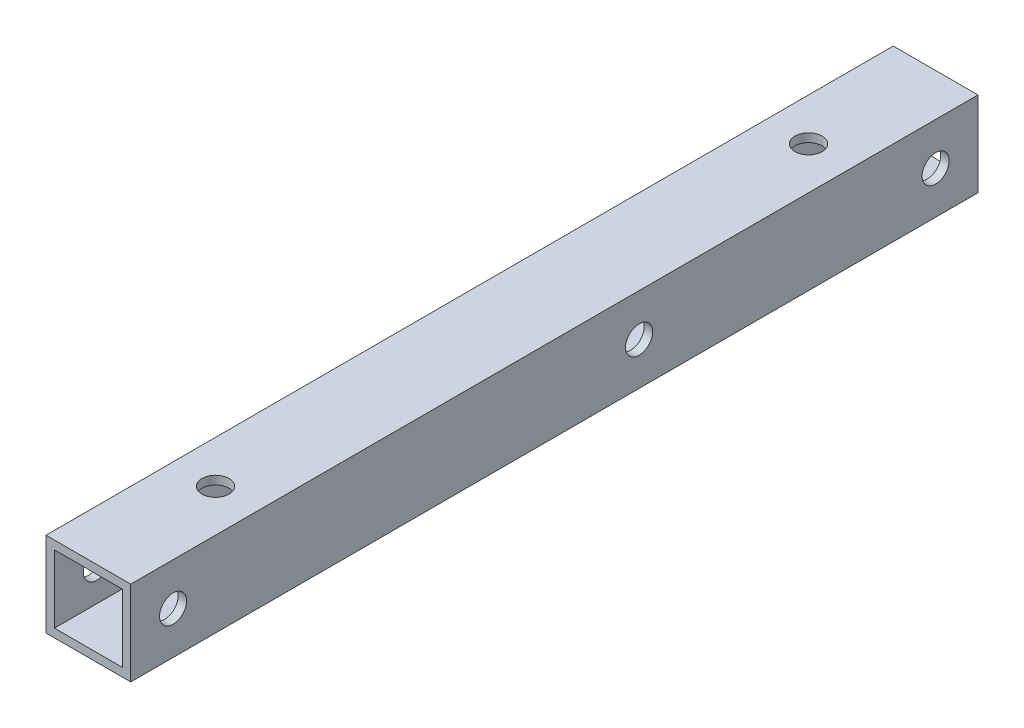
SolidWorks part; units mm, degrees
material "1060 合金"
ref_plane "正面" through (0, 0, 0) normal (0, 0, 1) x (1, 0, 0)
ref_plane "平面" through (0, 0, 0) normal (0, 1, 0) x (1, 0, 0)
ref_plane "右側面" through (0, 0, 0) normal (1, 0, 0) x (0, 0, -1)
sketch "ｽｹｯﾁ2" plane through (0, 0, 0) normal (0, 0, 1) x (1, 0, 0)
  line L1 (5, 5) -> (-5, 5)
  line L2 (5, 5) -> (5, -5)
  line L3 (5, -5) -> (-5, -5)
  line L4 (-5, 5) -> (-5, -5)
  line L5 (5, 5) -> (-5, -5) construction
  line L6 (5, -5) -> (-5, 5) construction
  point P0 (0, 0)
  dimension "D1" = 10
  dimension "D2" = 10
extrude "押し出し-薄板1" add sketch "ｽｹｯﾁ2" along normal blind 100 thin thin type one direction reverse wall 1
sketch "ｽｹｯﾁ3" plane through (5, 0, 0) normal (1, 0, 0) x (0, 0, -1)
  line L0 (-100, 0) -> (0, 0) construction
  line L1 (-100, -5) -> (-100, 5) construction
  line L2 (-50, 0) -> (-50, 5) construction
  line L3 (-100, 5) -> (0, 5) construction
  circle A0 centre (-95, 0) radius 1.6
  circle A3 centre (-5, 0) radius 1.6
  circle A4 centre (-40, 0) radius 1.6
  dimension "D1" = 5
  dimension "D2" = 35
  dimension "D3" = 3.2
  dimension "D4" = 3.2
extrude "ｶｯﾄ - 押し出し1" cut sketch "ｽｹｯﾁ3" against normal through all
sketch "ｽｹｯﾁ4" plane through (0, 5, 0) normal (0, 1, 0) x (1, 0, 0)
  line L0 (0, 0) -> (0, -100) construction
  line L1 (5, -100) -> (-5, -100) construction
  line L2 (5, 0) -> (-5, 0) construction
  circle A0 centre (0, -15) radius 1.6
  dimension "D3" = 3.2
  dimension "D4" = 15
extrude "ｶｯﾄ - 押し出し2" cut sketch "ｽｹｯﾁ4" against normal through all
sketch "ｽｹｯﾁ7" plane through (0, 5, 0) normal (0, 1, 0) x (1, 0, 0)
  line L0 (0, 0) -> (0, -100) construction
  line L1 (5, -100) -> (-5, -100) construction
  circle A0 centre (0, -85) radius 1.6
  dimension "D1" = 3.2
  dimension "D2" = 15
extrude "ｶｯﾄ - 押し出し4" cut sketch "ｽｹｯﾁ7" against normal through all
